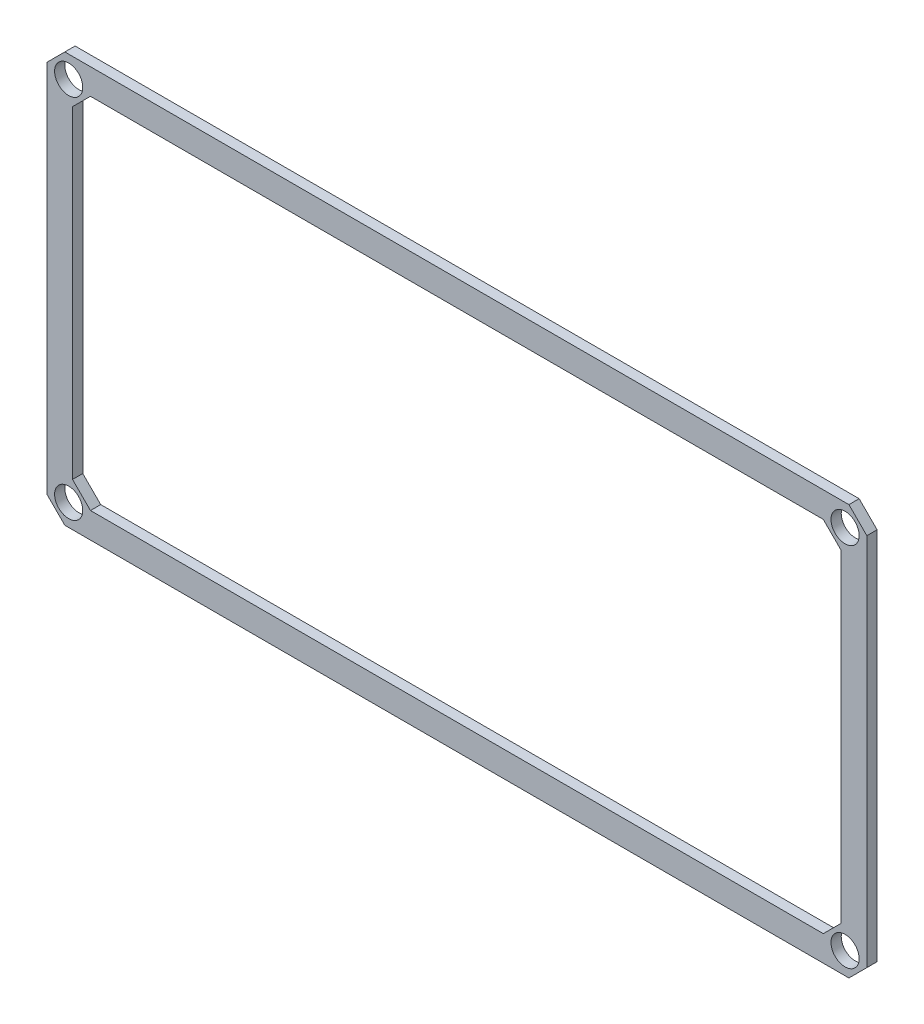
SolidWorks part; units mm, degrees
ref_plane "Front Plane" through (0, 0, 0) normal (0, 0, 1) x (1, 0, 0)
ref_plane "Top Plane" through (0, 0, 0) normal (0, 1, 0) x (1, 0, 0)
ref_plane "Right Plane" through (0, 0, 0) normal (1, 0, 0) x (0, 0, -1)
sketch "Sketch1" plane through (0, 0, 0) normal (0, 0, 1) x (1, 0, 0)
  line L0 (-75, 35) -> (75, 35)
  line L1 (-80, -40) -> (80, -40)
  line L2 (-80, -40) -> (-80, 40)
  line L3 (-80, 40) -> (80, 40)
  line L4 (80, -40) -> (80, 40)
  line L5 (-80, -40) -> (80, 40) construction
  line L6 (-80, 40) -> (80, -40) construction
  line L7 (75, -35) -> (75, 35)
  line L8 (-75, -35) -> (75, -35)
  line L9 (-75, -35) -> (-75, 35)
  point P0 (0, 0)
  dimension "D1" = 80
  dimension "D2" = 160
  dimension "D3" = 5
extrude "Boss-Extrude1" add sketch "Sketch1" along normal blind 2
chamfer "Chamfer1" distance 3.5 angle 45 8 edges at (80, -40, 1) (-80, -40, 1) (75, -35, 1) (75, 35, 1) (-75, 35, 1) (-75, -35, 1) (80, 40, 1) (-80, 40, 1)
hole_wizard "M5 Clearance Hole1" positions "Sketch2" profile "Sketch4" hole size "M5" standard "ANSI Metric" end condition through all
sketch "Sketch2" plane through (0, 0, 0) normal (0, 0, -1) x (-1, 0, 0)
  line L1 (75.75, -35.75) -> (-75.75, -35.75)
  line L2 (75.75, -35.75) -> (75.75, 35.75)
  line L3 (75.75, 35.75) -> (-75.75, 35.75)
  line L4 (-75.75, -35.75) -> (-75.75, 35.75)
  line L5 (75.75, -35.75) -> (-75.75, 35.75) construction
  line L6 (75.75, 35.75) -> (-75.75, -35.75) construction
  point P0 (0, 0)
  point P1 (-75.75, 35.75)
  point P126 (75.75, -35.75)
  point P127 (75.75, 35.75)
  point P128 (-75.75, -35.75)
  dimension "D1" = 71.5
  dimension "D2" = 151.5
sketch "Sketch4" plane through (0, 0, 0) normal (1, 0, 0) x (0, 1, 0)
  line L0 (0, 0) -> (0, 2)
  line L1 (0, 2) -> (2.75, 2)
  line L2 (2.75, 2) -> (2.75, 0)
  line L5 (2.75, 0) -> (0, 0)
  line L11 (0, -6.35) -> (0, 107.95) construction
  dimension "Thru Hole Dia." = 5.5
  dimension "Thru Hole Depth" = 2
